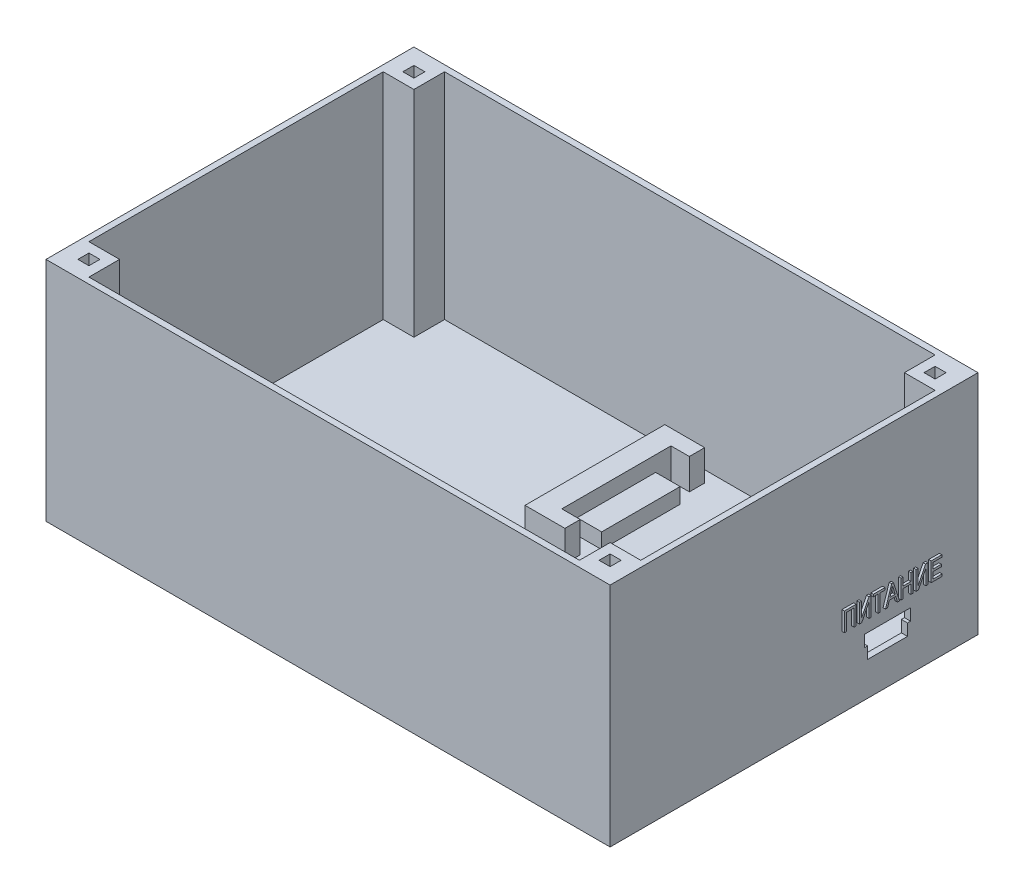
SolidWorks part; units mm, degrees
ref_plane "Спереди" through (0, 0, 0) normal (0, 0, 1) x (1, 0, 0)
ref_plane "Сверху" through (0, 0, 0) normal (0, 1, 0) x (1, 0, 0)
ref_plane "Справа" through (0, 0, 0) normal (1, 0, 0) x (0, 0, -1)
sketch "Эскиз2" plane through (0, 0, 0) normal (0, 1, 0) x (1, 0, 0)
  line L1 (0, 0) -> (92, 0)
  line L2 (0, 0) -> (0, 60)
  line L3 (0, 60) -> (92, 60)
  line L4 (92, 0) -> (92, 60)
extrude "Бобышка-Вытянуть1" add sketch "Эскиз2" along normal blind 2
sketch "Эскиз14" plane through (0, 2, 0) normal (0, 1, 0) x (1, 0, 0)
  line L0 (0, 60) -> (0, 0) construction
  line L1 (1, 59) -> (91, 59)
  line L2 (1, 59) -> (1, 1)
  line L3 (1, 1) -> (91, 1)
  line L4 (91, 59) -> (91, 1)
  line L5 (92, 60) -> (0, 60) construction
  line L6 (0, 0) -> (92, 0) construction
  line L7 (92, 0) -> (92, 60) construction
  line L9 (92, 0) -> (0, 0)
  line L10 (92, 0) -> (92, 60)
  line L11 (92, 60) -> (0, 60)
  line L12 (0, 0) -> (0, 60)
  dimension "D1" = 1
  dimension "D2" = 1
  dimension "D3" = 1
  dimension "D4" = 1
extrude "Бобышка-Вытянуть9" add sketch "Эскиз14" along normal blind 35 separate body
sketch "Эскиз16" plane through (0, 2, 0) normal (0, 1, 0) x (1, 0, 0)
  line L0 (1, 56.5) -> (6, 56.5) construction
  line L1 (6, 54) -> (1, 54)
  line L2 (6, 54) -> (6, 59)
  line L3 (6, 59) -> (1, 59)
  line L4 (1, 54) -> (1, 59)
  line L5 (3.5, 54) -> (3.5, 59) construction
  line L6 (86, 3.5) -> (91, 3.5) construction
  line L11 (91, 1) -> (86, 1)
  line L12 (91, 1) -> (91, 6)
  line L17 (91, 6) -> (86, 6)
  line L18 (86, 1) -> (86, 6)
  line L23 (88.5, 1) -> (88.5, 6) construction
  line L24 (1, 3.5) -> (6, 3.5) construction
  line L25 (6, 1) -> (1, 1)
  line L26 (6, 1) -> (6, 6)
  line L27 (6, 6) -> (1, 6)
  line L28 (1, 1) -> (1, 6)
  line L29 (3.5, 1) -> (3.5, 6) construction
  line L30 (86, 56.5) -> (91, 56.5) construction
  line L31 (91, 54) -> (86, 54)
  line L32 (91, 54) -> (91, 59)
  line L33 (91, 59) -> (86, 59)
  line L34 (86, 54) -> (86, 59)
  line L35 (88.5, 54) -> (88.5, 59) construction
  line L36 (88.5, 57.4) -> (88.5, 55.6) construction
  line L37 (87.6, 57.4) -> (89.4, 57.4)
  line L38 (87.6, 57.4) -> (87.6, 55.6)
  line L39 (87.6, 55.6) -> (89.4, 55.6)
  line L40 (89.4, 57.4) -> (89.4, 55.6)
  line L41 (87.6, 56.5) -> (89.4, 56.5) construction
  line L42 (3.5, 57.4) -> (3.5, 55.6) construction
  line L47 (2.6, 57.4) -> (4.4, 57.4)
  line L48 (2.6, 57.4) -> (2.6, 55.6)
  line L53 (2.6, 55.6) -> (4.4, 55.6)
  line L54 (4.4, 57.4) -> (4.4, 55.6)
  line L59 (2.6, 56.5) -> (4.4, 56.5) construction
  line L60 (3.5, 4.4) -> (3.5, 2.6) construction
  line L61 (2.6, 4.4) -> (4.4, 4.4)
  line L62 (2.6, 4.4) -> (2.6, 2.6)
  line L63 (2.6, 2.6) -> (4.4, 2.6)
  line L64 (4.4, 4.4) -> (4.4, 2.6)
  line L65 (2.6, 3.5) -> (4.4, 3.5) construction
  line L66 (88.5, 4.4) -> (88.5, 2.6) construction
  line L67 (87.6, 4.4) -> (89.4, 4.4)
  line L68 (87.6, 4.4) -> (87.6, 2.6)
  line L69 (87.6, 2.6) -> (89.4, 2.6)
  line L70 (89.4, 4.4) -> (89.4, 2.6)
  line L71 (87.6, 3.5) -> (89.4, 3.5) construction
  dimension "D2" = 5
  dimension "D3" = 5
  dimension "D5" = 5
  dimension "D6" = 5
  dimension "D8" = 5
  dimension "D9" = 5
  dimension "D11" = 5
  dimension "D12" = 5
sketch "Эскиз17" plane through (92, 0, 0) normal (1, 0, 0) x (0, 0, -1)
  line L0 (41.5, 9.3) -> (49, 9.3)
  line L1 (49, 9.3) -> (49, 7.4)
  line L2 (49, 7.4) -> (48.5, 7.4)
  line L3 (48.5, 7.4) -> (48.5, 5.5)
  line L4 (48.5, 5.5) -> (42, 5.5)
  line L5 (42, 5.5) -> (42, 7.4)
  line L6 (42, 7.4) -> (41.5, 7.4)
  line L7 (41.5, 7.4) -> (41.5, 9.3)
  line L8 (0, 2) -> (60, 2) construction
  line L9 (59, 37) -> (59, 2) construction
  dimension "D1" = 7.5
  dimension "D2" = 6.5
  dimension "D3" = 3.8
  dimension "D4" = 1.9
  dimension "D5" = 3.5
  dimension "D6" = 10
sketch "Эскиз18" plane through (0, 2, 0) normal (0, 1, 0) x (1, 0, 0)
  line L0 (91, 1) -> (91, 59) construction
  line L1 (47.3, 52.1241) -> (51.3, 52.1241)
  line L2 (47.3, 52.1241) -> (47.3, 39.3241)
  line L3 (47.3, 39.3241) -> (51.3, 39.3241)
  line L4 (51.3, 52.1241) -> (51.3, 39.3241)
  dimension "D1" = 12.8
  dimension "D2" = 4
  dimension "D3" = 43.7
extrude "Бобышка-Вытянуть12" add sketch "Эскиз18" along normal blind 2.5
sketch "Эскиз19" plane through (0, 2, 0) normal (0, 1, 0) x (1, 0, 0)
  line L1 (47.3, 39.3241) -> (50.3, 39.3241)
  line L2 (47.3, 39.3241) -> (47.3, 36.8241)
  line L3 (47.3, 36.8241) -> (50.3, 36.8241)
  line L4 (50.3, 39.3241) -> (50.3, 36.8241)
  line L5 (47.3, 52.1241) -> (50.3, 52.1241)
  line L6 (47.3, 52.1241) -> (47.3, 54.6241)
  line L7 (47.3, 54.6241) -> (50.3, 54.6241)
  line L8 (50.3, 52.1241) -> (50.3, 54.6241)
sketch "Эскиз20" plane through (0, 2, 0) normal (0, 1, 0) x (1, 0, 0)
  line L0 (47.3, 52.1241) -> (47.3, 39.3241) construction
  line L1 (47.3, 54.6241) -> (43.8, 54.6241)
  line L2 (47.3, 54.6241) -> (47.3, 36.8241)
  line L3 (47.3, 36.8241) -> (43.8, 36.8241)
  line L4 (43.8, 54.6241) -> (43.8, 36.8241)
extrude "Бобышка-Вытянуть14" add sketch "Эскиз20" along normal blind 5
extrude "Вырез-Вытянуть1" cut sketch "Эскиз17" against normal blind 5 contours L0 L1 L2 L3 L4 L5 L6 L7
sketch "Эскиз21" plane through (0, 2, 0) normal (0, 1, 0) x (1, 0, 0)
  line L0 (1, 6) -> (3.7061, 6)
  line L1 (88.2939, 6) -> (91, 6)
  line L2 (88.2939, 6) -> (88.2939, 26.3)
  line L3 (88.2939, 26.3) -> (91, 26.3)
  line L4 (91, 6) -> (91, 26.3)
  line L5 (1, 6) -> (1, 26.3)
  line L6 (1, 26.3) -> (3.7061, 26.3)
  line L7 (3.7061, 6) -> (3.7061, 26.3)
  line L9 (1, 59) -> (1, 1) construction
  line L11 (6, 6) -> (1, 6) construction
  dimension "D1" = 20.3
  dimension "D2" = 90
extrude "Бобышка-Вытянуть16" add sketch "Эскиз21" along normal blind 2.5
sketch "Эскиз22" plane through (0, 2, 0) normal (0, 1, 0) x (1, 0, 0)
  line L0 (1, 59) -> (1, 26.3) construction
  line L1 (3.7061, 26.3) -> (1, 26.3)
  line L2 (3.7061, 26.3) -> (3.7061, 28.8)
  line L3 (3.7061, 28.8) -> (1, 28.8)
  line L4 (1, 26.3) -> (1, 28.8)
  line L6 (91, 26.3) -> (88.2939, 26.3)
  line L7 (91, 26.3) -> (91, 28.8)
  line L8 (91, 28.8) -> (88.2939, 28.8)
  line L9 (88.2939, 26.3) -> (88.2939, 28.8)
extrude "Бобышка-Вытянуть17" add sketch "Эскиз22" along normal blind 5
extrude "Бобышка-Вытянуть19" add sketch "Эскиз16" along normal blind 35
sketch "Эскиз23" plane through (92, 0, 0) normal (1, 0, 0) x (0, 0, -1)
  text T0 "ПИТАНИЕ" font "Arial" height in points 12
extrude "Бобышка-Вытянуть20" add sketch "Эскиз23" along normal blind 0.4
sketch "Эскиз24" plane through (1, 0, 0) normal (1, 0, 0) x (0, 0, -1)
  line L0 (26.3, 4.5) -> (6, 4.5) construction
  line L1 (12.8962, 14.1) -> (22.5962, 14.1)
  line L2 (12.8962, 14.1) -> (12.8962, 9.5)
  line L3 (12.8962, 9.5) -> (22.5962, 9.5)
  line L4 (22.5962, 14.1) -> (22.5962, 9.5)
  dimension "D1" = 9.7
  dimension "D2" = 4.6
  dimension "D3" = 5
extrude "Вырез-Вытянуть2" cut sketch "Эскиз24" against normal blind 1 contours L2 L1 L4 L3
sketch "Эскиз25" plane through (0, 0, 0) normal (-1, 0, 0) x (0, 0, 1)
  text T0 "UART"
extrude "Бобышка-Вытянуть21" add sketch "Эскиз25" along normal blind 0.4
sketch "Эскиз26" plane through (0, 2, 0) normal (0, 1, 0) x (1, 0, 0)
  line L1 (43.8, 54.6241) -> (50.3, 54.6241)
  line L2 (43.8, 54.6241) -> (43.8, 57.1241)
  line L3 (43.8, 57.1241) -> (50.3, 57.1241)
  line L4 (50.3, 54.6241) -> (50.3, 57.1241)
  line L5 (43.8, 36.8241) -> (50.3, 36.8241)
  line L6 (43.8, 36.8241) -> (43.8, 34.3241)
  line L7 (43.8, 34.3241) -> (50.3, 34.3241)
  line L8 (50.3, 36.8241) -> (50.3, 34.3241)
extrude "Бобышка-Вытянуть22" add sketch "Эскиз26" along normal blind 5
